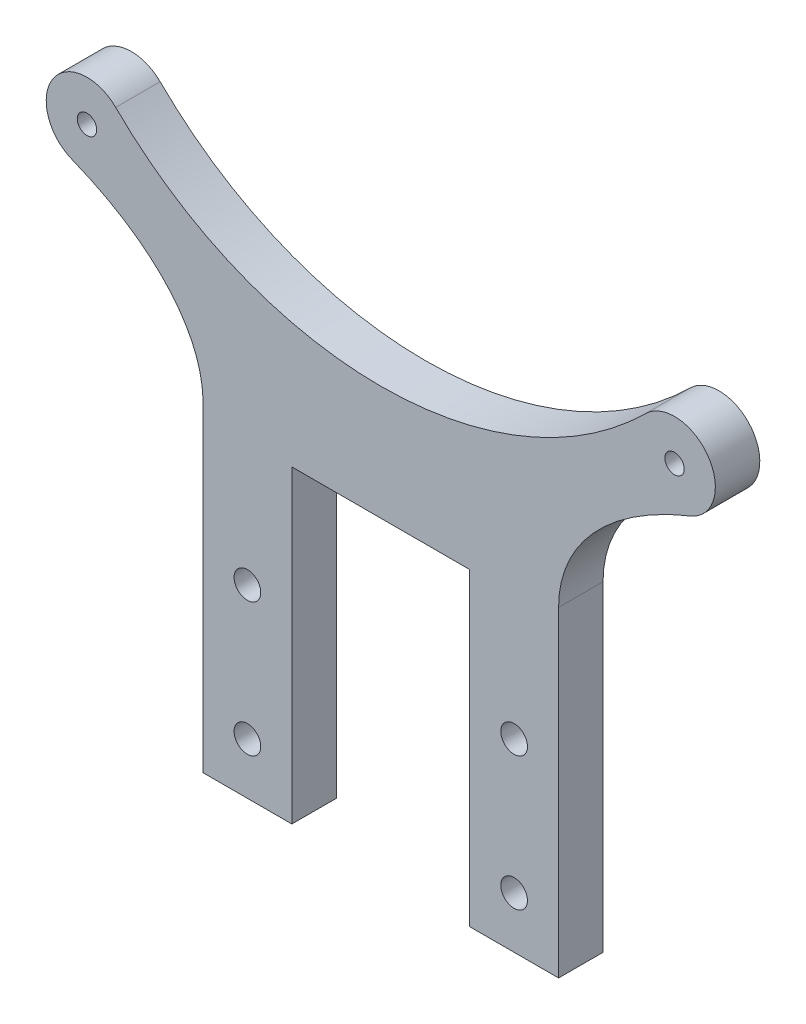
SolidWorks part; units mm, degrees
ref_plane "Front Plane" through (0, 0, 0) normal (0, 0, 1) x (1, 0, 0)
ref_plane "Top Plane" through (0, 0, 0) normal (0, 1, 0) x (1, 0, 0)
ref_plane "Right Plane" through (0, 0, 0) normal (1, 0, 0) x (0, 0, -1)
sketch "Sketch1" plane through (0, 0, 0) normal (0, 0, 1) x (1, 0, 0)
  line L0 (0, 32.7025) -> (0, -57.25) construction
  line L1 (-12.7, 0) -> (12.7, 0)
  line L2 (-12.7, 0) -> (-12.7, -44.1799)
  line L3 (-25.4, -44.1799) -> (-12.7, -44.1799)
  line L4 (-25.4, 1.6703) -> (-25.4, -44.1799)
  line L5 (25.4, 1.6703) -> (25.4, -44.1799)
  line L6 (25.4, -44.1799) -> (12.7, -44.1799)
  line L7 (12.7, 0) -> (12.7, -44.1799)
  circle A0 centre (41.9643, 27.7449) radius 1.3891
  arc A1 (-37.8652, 31.8895) -> (-44.1259, 22.3312) centre (-41.9643, 27.7449) ccw
  arc A2 (37.8652, 31.8895) -> (-37.8652, 31.8895) centre (0, 70.1756) cw
  arc A3 (37.8652, 31.8895) -> (44.1259, 22.3312) centre (41.9643, 27.7449) cw
  circle A4 centre (-41.9643, 27.7449) radius 1.3891
  circle A5 centre (-19.05, -17.78) radius 1.905
  circle A6 centre (-19.05, -36.83) radius 1.905
  circle A7 centre (19.05, -36.83) radius 1.905
  circle A8 centre (19.05, -17.78) radius 1.905
  ellipse E0 centre (-68.6622, 1.6703) end of major axis (-25.4, 1.6703) minor radius 25.0857 (-44.1259, 22.3312) -> (-25.4, 1.6703) cw
  ellipse E1 centre (68.6622, 1.6703) end of major axis (25.4, 1.6703) minor radius 25.0857 (44.1259, 22.3312) -> (25.4, 1.6703) ccw
  point P9 (-41.9643, 27.7449)
  point P14 (0, 16.3277)
  point P28 (0, 0)
  point P34 (0, 0)
  dimension "D4" = 19.05
  dimension "D5" = 3.81
  dimension "D1" = 12.7
  dimension "D2" = 25.4
  dimension "D3" = 17.78
extrude "Boss-Extrude1" add sketch "Sketch1" along normal blind 6.35
